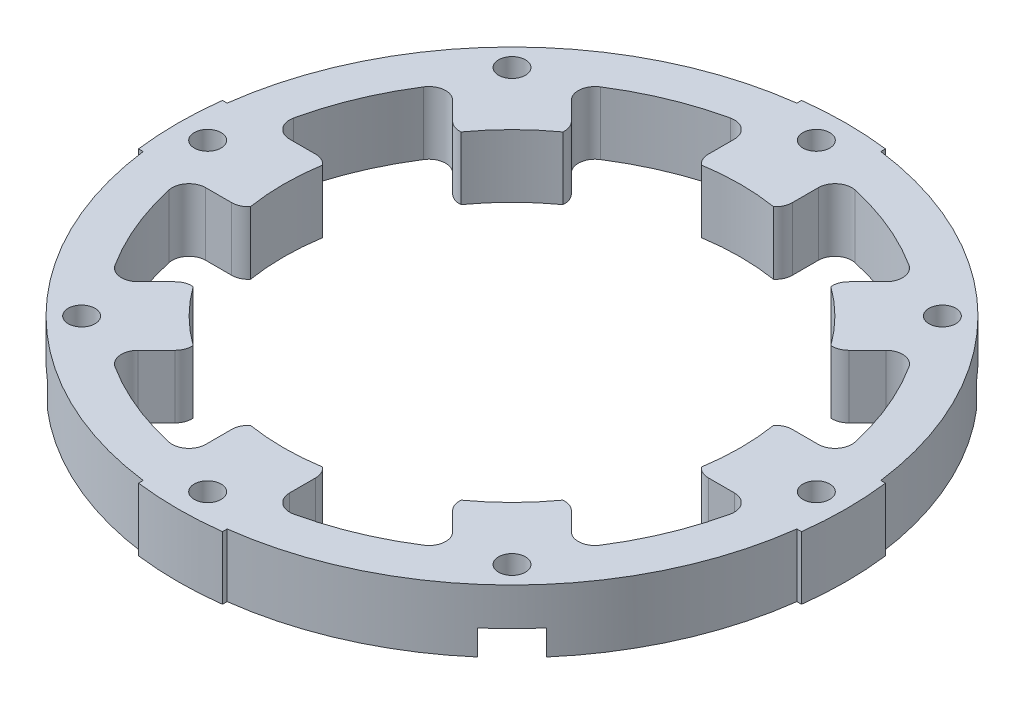
SolidWorks part; units mm, degrees
ref_plane "Front Plane" through (0, 0, 0) normal (0, 0, 1) x (1, 0, 0)
ref_plane "Top Plane" through (0, 0, 0) normal (0, 1, 0) x (1, 0, 0)
ref_plane "Right Plane" through (0, 0, 0) normal (1, 0, 0) x (0, 0, -1)
sketch "Sketch1" plane through (0, 0, 0) normal (0, 1, 0) x (1, 0, 0)
  line L0 (0, 0) -> (44.25, 0) construction
  line L1 (28.3831, 5) -> (31.4811, 5)
  line L2 (28.3831, -5) -> (31.4811, -5)
  line L3 (26.3831, 3) -> (26.3831, -3)
  line L4 (23.6054, -16.5343) -> (25.7961, -18.725)
  line L5 (20.777, -16.5343) -> (16.5343, -20.777)
  line L6 (16.5343, -23.6054) -> (18.725, -25.7961)
  line L7 (5, -28.3831) -> (5, -31.4811)
  line L8 (3, -26.3831) -> (-3, -26.3831)
  line L9 (-5, -28.3831) -> (-5, -31.4811)
  line L10 (-16.5343, -23.6054) -> (-18.725, -25.7961)
  line L11 (-16.5343, -20.777) -> (-20.777, -16.5343)
  line L12 (-23.6054, -16.5343) -> (-25.7961, -18.725)
  line L13 (-28.3831, -5) -> (-31.4811, -5)
  line L14 (-26.3831, -3) -> (-26.3831, 3)
  line L15 (-28.3831, 5) -> (-31.4811, 5)
  line L16 (-23.6054, 16.5343) -> (-25.7961, 18.725)
  line L17 (-20.777, 16.5343) -> (-16.5343, 20.777)
  line L18 (-16.5343, 23.6054) -> (-18.725, 25.7961)
  line L19 (-5, 28.3831) -> (-5, 31.4811)
  line L20 (-3, 26.3831) -> (3, 26.3831)
  line L21 (5, 28.3831) -> (5, 31.4811)
  line L22 (16.5343, 23.6054) -> (18.725, 25.7961)
  line L23 (16.5343, 20.777) -> (20.777, 16.5343)
  line L24 (23.6054, 16.5343) -> (25.7961, 18.725)
  line L25 (-5, 33.8831) -> (-5, 46.441) construction
  line L26 (5, 33.8831) -> (5, 47.4442) construction
  line L27 (-5, 38.9302) -> (-5, 39.4847)
  line L28 (5, 38.9302) -> (5, 39.4847)
  line L29 (38.9302, -5) -> (39.4847, -5)
  line L30 (38.9302, 5) -> (39.4847, 5)
  line L31 (-5, -38.9302) -> (-5, -39.4847)
  line L32 (5, -38.9302) -> (5, -39.4847)
  line L33 (-38.9302, 5) -> (-39.4847, 5)
  line L34 (-38.9302, -5) -> (-39.4847, -5)
  arc A0 (-38.9302, -5) -> (-5, -38.9302) centre (0, 0) ccw
  circle A1 centre (0, 0) radius 36.25 construction
  circle A2 centre (36.25, 0) radius 1.6
  arc A3 (33.4335, 7.4341) -> (28.8977, 18.3843) centre (0, 0) ccw
  circle A4 centre (25.6326, -25.6326) radius 1.6
  circle A5 centre (0, -36.25) radius 1.6
  circle A6 centre (-25.6326, -25.6326) radius 1.6
  circle A7 centre (-36.25, 0) radius 1.6
  circle A8 centre (-25.6326, 25.6326) radius 1.6
  circle A9 centre (0, 36.25) radius 1.6
  circle A10 centre (25.6326, 25.6326) radius 1.6
  arc A11 (-7.4341, 33.4335) -> (-18.3843, 28.8977) centre (0, 0) ccw
  arc A12 (18.3843, 28.8977) -> (7.4341, 33.4335) centre (0, 0) ccw
  arc A13 (-28.8977, 18.3843) -> (-33.4335, 7.4341) centre (0, 0) ccw
  arc A14 (-33.4335, -7.4341) -> (-28.8977, -18.3843) centre (0, 0) ccw
  arc A15 (-18.3843, -28.8977) -> (-7.4341, -33.4335) centre (0, 0) ccw
  arc A16 (7.4341, -33.4335) -> (18.3843, -28.8977) centre (0, 0) ccw
  arc A17 (28.8977, -18.3843) -> (33.4335, -7.4341) centre (0, 0) ccw
  arc A18 (-39.4847, 5) -> (-39.4847, -5) centre (0, 0) ccw
  arc A19 (-5, -39.4847) -> (5, -39.4847) centre (0, 0) ccw
  arc A20 (-5, 38.9302) -> (-38.9302, 5) centre (0, 0) ccw
  arc A21 (5, 39.4847) -> (-5, 39.4847) centre (0, 0) ccw
  arc A22 (38.9302, 5) -> (5, 38.9302) centre (0, 0) ccw
  arc A23 (39.4847, -5) -> (39.4847, 5) centre (0, 0) ccw
  arc A24 (5, -38.9302) -> (38.9302, -5) centre (0, 0) ccw
  arc A25 (-31.4811, -5) -> (-33.4335, -7.4341) centre (-31.4811, -7) ccw
  arc A26 (-31.4811, 5) -> (-33.4335, 7.4341) centre (-31.4811, 7) cw
  arc A27 (-25.7961, 18.725) -> (-28.8977, 18.3843) centre (-27.2103, 17.3108) ccw
  arc A28 (-18.725, 25.7961) -> (-18.3843, 28.8977) centre (-17.3108, 27.2103) cw
  arc A29 (-5, 31.4811) -> (-7.4341, 33.4335) centre (-7, 31.4811) ccw
  arc A30 (5, 31.4811) -> (7.4341, 33.4335) centre (7, 31.4811) cw
  arc A31 (18.725, 25.7961) -> (18.3843, 28.8977) centre (17.3108, 27.2103) ccw
  arc A32 (25.7961, 18.725) -> (28.8977, 18.3843) centre (27.2103, 17.3108) cw
  arc A33 (31.4811, 5) -> (33.4335, 7.4341) centre (31.4811, 7) ccw
  arc A34 (31.4811, -5) -> (33.4335, -7.4341) centre (31.4811, -7) cw
  arc A35 (25.7961, -18.725) -> (28.8977, -18.3843) centre (27.2103, -17.3108) ccw
  arc A36 (18.725, -25.7961) -> (18.3843, -28.8977) centre (17.3108, -27.2103) cw
  arc A37 (5, -31.4811) -> (7.4341, -33.4335) centre (7, -31.4811) ccw
  arc A38 (-5, -31.4811) -> (-7.4341, -33.4335) centre (-7, -31.4811) cw
  arc A39 (-18.725, -25.7961) -> (-18.3843, -28.8977) centre (-17.3108, -27.2103) ccw
  arc A40 (-25.7961, -18.725) -> (-28.8977, -18.3843) centre (-27.2103, -17.3108) cw
  arc A41 (-28.3831, -5) -> (-26.3831, -3) centre (-28.3831, -3) ccw
  arc A42 (-26.3831, 3) -> (-28.3831, 5) centre (-28.3831, 3) ccw
  arc A43 (-23.6054, 16.5343) -> (-20.777, 16.5343) centre (-22.1912, 17.9485) ccw
  arc A44 (-16.5343, 20.777) -> (-16.5343, 23.6054) centre (-17.9485, 22.1912) ccw
  arc A45 (-5, 28.3831) -> (-3, 26.3831) centre (-3, 28.3831) ccw
  arc A46 (3, 26.3831) -> (5, 28.3831) centre (3, 28.3831) ccw
  arc A47 (16.5343, 23.6054) -> (16.5343, 20.777) centre (17.9485, 22.1912) ccw
  arc A48 (20.777, 16.5343) -> (23.6054, 16.5343) centre (22.1912, 17.9485) ccw
  arc A49 (28.3831, 5) -> (26.3831, 3) centre (28.3831, 3) ccw
  arc A50 (28.3831, -5) -> (26.3831, -3) centre (28.3831, -3) cw
  arc A51 (23.6054, -16.5343) -> (20.777, -16.5343) centre (22.1912, -17.9485) ccw
  arc A52 (16.5343, -20.777) -> (16.5343, -23.6054) centre (17.9485, -22.1912) ccw
  arc A53 (5, -28.3831) -> (3, -26.3831) centre (3, -28.3831) ccw
  arc A54 (-3, -26.3831) -> (-5, -28.3831) centre (-3, -28.3831) ccw
  arc A55 (-16.5343, -23.6054) -> (-16.5343, -20.777) centre (-17.9485, -22.1912) ccw
  arc A56 (-20.777, -16.5343) -> (-23.6054, -16.5343) centre (-22.1912, -17.9485) ccw
  point P55 (0, 0)
  point P76 (0, 0)
  point P92 (33.8831, 5)
  point P95 (33.8831, -5)
  point P126 (26.3831, 5)
  point P129 (26.3831, -5)
  dimension "D1" = 78.5
  dimension "D2" = 72.5
  dimension "D3" = 3.2
  dimension "D4" = 5
  dimension "D8" = 79.6
  dimension "D10" = 2
  dimension "D11" = 2
  dimension "D5" = 7.5
  dimension "D6" = 10
  dimension "D7" = 8
  dimension "D9" = 4
extrude "Boss-Extrude1" add sketch "Sketch1" along normal blind 7.5
sketch "Sketch3" plane through (0, 7.5, 0) normal (0, 1, 0) x (1, 0, 0)
  circle A0 centre (0, 0) radius 27.2
  dimension "D1" = 54.4
extrude "Cut-Extrude1" cut sketch "Sketch3" against normal blind 7.5
sketch "Sketch4" plane through (0, 0, 0) normal (0, -1, 0) x (1, 0, 0)
  circle A0 centre (25.6326, -25.6326) radius 4.1
  circle A1 centre (-25.6326, -25.6326) radius 4.1
  circle A2 centre (-25.6326, 25.6326) radius 4.1
  circle A3 centre (25.6326, 25.6326) radius 4.1
  point P12 (0, 0)
  dimension "D1" = 8.2
  dimension "D2" = 4
extrude "Cut-Extrude2" cut sketch "Sketch4" against normal blind 3
